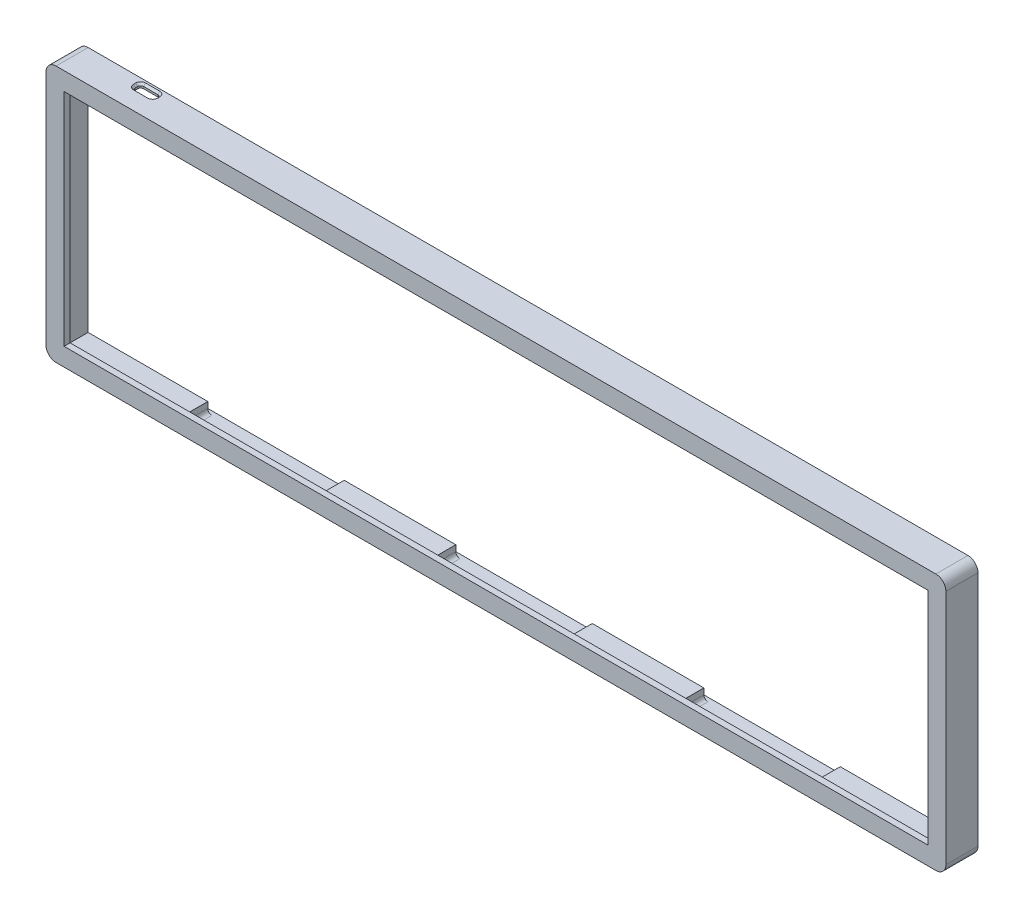
SolidWorks part; units mm, degrees
ref_plane "Front Plane" through (0, 0, 0) normal (0, 0, 1) x (1, 0, 0)
ref_plane "Top Plane" through (0, 0, 0) normal (0, 1, 0) x (1, 0, 0)
ref_plane "Right Plane" through (0, 0, 0) normal (1, 0, 0) x (0, 0, -1)
sketch "Sketch1" plane through (0, 0, 0) normal (0, 0, 1) x (1, 0, 0)
  line L0 (306.936, 114) -> (374.936, 114)
  line L1 (0, 0) -> (434.581, 0)
  line L2 (0, 0) -> (0, 114)
  line L3 (0, 114) -> (434.581, 114)
  line L4 (434.581, 0) -> (434.581, 114)
  line L5 (-2, -7) -> (436.581, -7)
  line L6 (-7, -2) -> (-7, 116)
  line L7 (-2, 121) -> (436.581, 121)
  line L8 (441.581, -2) -> (441.581, 116)
  line L9 (374.936, 114) -> (306.936, 114)
  line L10 (374.936, 114) -> (374.936, 117)
  line L11 (372.936, 119) -> (308.936, 119)
  line L12 (306.936, 114) -> (306.936, 117)
  line L13 (183.291, 114) -> (251.291, 114)
  line L14 (251.291, 114) -> (183.291, 114)
  line L15 (251.291, 114) -> (251.291, 117)
  line L16 (249.291, 119) -> (185.291, 119)
  line L17 (183.291, 114) -> (183.291, 117)
  line L18 (59.646, 0) -> (127.646, 0)
  line L19 (59.646, 0) -> (127.646, 0)
  line L20 (59.646, 0) -> (59.646, -3)
  line L21 (61.646, -5) -> (125.646, -5)
  line L22 (127.646, 0) -> (127.646, -3)
  line L23 (59.646, 114) -> (127.646, 114)
  line L24 (127.646, 114) -> (59.646, 114)
  line L25 (127.646, 114) -> (127.646, 117)
  line L26 (125.646, 119) -> (61.646, 119)
  line L27 (59.646, 114) -> (59.646, 117)
  line L29 (183.291, 0) -> (251.291, 0)
  line L30 (183.291, 0) -> (183.291, -3)
  line L31 (185.291, -5) -> (249.291, -5)
  line L32 (251.291, 0) -> (251.291, -3)
  line L33 (306.936, 0) -> (374.936, 0)
  line L34 (306.936, 0) -> (306.936, -3)
  line L35 (308.936, -5) -> (372.936, -5)
  line L36 (374.936, 0) -> (374.936, -3)
  arc A0 (372.936, 119) -> (374.936, 117) centre (372.936, 117) cw
  arc A1 (308.936, 119) -> (306.936, 117) centre (308.936, 117) ccw
  arc A2 (249.291, 119) -> (251.291, 117) centre (249.291, 117) cw
  arc A3 (185.291, 119) -> (183.291, 117) centre (185.291, 117) ccw
  arc A4 (125.646, -5) -> (127.646, -3) centre (125.646, -3) ccw
  arc A5 (61.646, -5) -> (59.646, -3) centre (61.646, -3) cw
  arc A6 (125.646, 119) -> (127.646, 117) centre (125.646, 117) cw
  arc A7 (61.646, 119) -> (59.646, 117) centre (61.646, 117) ccw
  arc A8 (249.291, -5) -> (251.291, -3) centre (249.291, -3) ccw
  arc A9 (183.291, -3) -> (185.291, -5) centre (185.291, -3) ccw
  arc A10 (372.936, -5) -> (374.936, -3) centre (372.936, -3) ccw
  arc A11 (306.936, -3) -> (308.936, -5) centre (308.936, -3) ccw
  arc A12 (-2, -7) -> (-7, -2) centre (-2, -2) cw
  arc A13 (436.581, -7) -> (441.581, -2) centre (436.581, -2) ccw
  arc A14 (436.581, 121) -> (441.581, 116) centre (436.581, 116) cw
  arc A15 (-7, 116) -> (-2, 121) centre (-2, 116) cw
  point P15 (374.936, 119)
  point P18 (306.936, 119)
  point P33 (127.646, -5)
  point P44 (59.646, -5)
  dimension "D10" = 2
  dimension "D19" = 2
  dimension "D20" = 2
  dimension "D21" = 2
  dimension "D22" = 5
  dimension "D1" = 434.581
  dimension "D2" = 114
  dimension "D3" = 7
  dimension "D4" = 7
  dimension "D5" = 7
  dimension "D6" = 7
  dimension "D7" = 68
  dimension "D8" = 59.645
  dimension "D9" = 5
  dimension "D11" = 0
  dimension "D12" = 55.645
  dimension "D13" = 55.645
  dimension "D14" = 0
  dimension "D15" = 5
  dimension "D16" = 5
  dimension "D17" = 68
  dimension "D18" = 5
extrude "Boss-Extrude1" add sketch "Sketch1" along normal blind 16 contours A15 L6 A12 L5 A13 L8 A14 L7 A11 L34 L1 L32 A8 L31 A9 L30 L22 A4 L21 A5 L20 L2 L3 L27 A7 L26 A6 L25 L17 A3 L16 A2 L15 L12 A1 L11 A0 L10 L4 L36 A10 L35
sketch "Sketch2" plane through (0, 0, 16) normal (0, 0, 1) x (1, 0, 0)
  line L1 (-2, 121) -> (436.581, 121)
  line L2 (-2, 121) -> (-2, -7)
  line L3 (-2, -7) -> (436.581, -7)
  line L4 (436.581, 121) -> (436.581, -7)
  line L10 (127.646, 114) -> (183.291, 114) construction
  line L11 (2, 112) -> (432.581, 112)
  line L12 (2, 112) -> (2, 2)
  line L13 (2, 2) -> (432.581, 2)
  line L14 (432.581, 112) -> (432.581, 2)
  line L15 (0, 0) -> (0, 114) construction
  line L16 (434.581, 0) -> (434.581, 114) construction
  line L17 (374.936, 0) -> (434.581, 0) construction
  dimension "D1" = 2
  dimension "D2" = 2
  dimension "D3" = 2
  dimension "D4" = 2
extrude "Boss-Extrude2" add sketch "Sketch2" against normal blind 3
sketch "Sketch3" plane through (0, 0, 0) normal (0, 0, -1) x (-1, 0, 0)
  line L0 (-372.936, 119) -> (-308.936, 119) construction
  line L1 (-437.581, 119) -> (3.0013, 119)
  line L2 (-437.581, 119) -> (-437.581, -5)
  line L3 (-437.581, -5) -> (3.0013, -5)
  line L4 (3.0013, 119) -> (3.0013, -5)
  line L5 (-434.581, 0) -> (-434.581, 114) construction
  line L6 (0, 0) -> (0, 114) construction
  line L7 (0, 0) -> (-59.646, 0) construction
  dimension "D1" = 0
  dimension "D2" = 3
  dimension "D3" = 3.0013
  dimension "D4" = 5
extrude "Cut-Extrude1" cut sketch "Sketch3" against normal blind 2
sketch "Sketch4" plane through (0, 0, 2) normal (0, 0, -1) x (-1, 0, 0)
  line L0 (-251.291, 114) -> (-306.936, 114) construction
  line L1 (-279.1135, 114) -> (-279.1135, 119) construction
  line L2 (-249.291, 119) -> (-308.936, 119) construction
  line L3 (-155.4685, 114) -> (-155.4685, 119) construction
  line L4 (-127.646, 114) -> (-183.291, 114) construction
  line L5 (-125.646, 119) -> (-185.291, 119) construction
  line L6 (-279.1135, -5) -> (-279.1135, 0) construction
  line L7 (-308.936, -5) -> (-249.291, -5) construction
  line L8 (-306.936, 0) -> (-251.291, 0) construction
  line L9 (-155.4685, 0) -> (-155.4685, -5) construction
  line L10 (-183.291, 0) -> (-127.646, 0) construction
  line L11 (-185.291, -5) -> (-125.646, -5) construction
  line L12 (-2, 2) -> (-2, 0) construction
  line L13 (-59.646, 0) -> (0, 0) construction
  line L14 (-2, 0) -> (-2, -5) construction
  line L15 (3.0013, -5) -> (-437.581, -5) construction
  line L16 (-2, 112) -> (-2, 114) construction
  line L17 (-59.646, 114) -> (0, 114) construction
  line L18 (-2, 114) -> (-2, 119) construction
  line L19 (-437.581, 119) -> (3.0013, 119) construction
  line L20 (-432.581, 112) -> (-432.581, 114) construction
  line L21 (-374.936, 114) -> (-434.581, 114) construction
  line L22 (-432.581, 114) -> (-432.581, 119) construction
  line L23 (-372.936, 119) -> (-437.581, 119) construction
  line L24 (-432.581, 2) -> (-432.581, 0) construction
  line L25 (-374.936, 0) -> (-434.581, 0) construction
  line L26 (-432.581, 0) -> (-432.581, -5) construction
  line L27 (-437.581, -5) -> (-372.936, -5) construction
  circle A0 centre (-279.1135, 116.5) radius 1.05
  circle A1 centre (-155.4685, 116.5) radius 1.05
  circle A2 centre (-279.1135, -2.5) radius 1.05
  circle A3 centre (-155.4685, -2.5) radius 1.05
  circle A4 centre (-2, -2.5) radius 1.05
  circle A5 centre (-2, 116.5) radius 1.05
  circle A6 centre (-432.581, 116.5) radius 1.05
  circle A7 centre (-432.581, -2.5) radius 1.05
extrude "Cut-Extrude2" cut sketch "Sketch4" against normal blind 2.5
sketch "Sketch5" plane through (0, 0, 2) normal (0, 0, -1) x (-1, 0, 0)
  line L0 (0, 114) -> (-59.646, 114) construction
  line L1 (-17, 114) -> (-47, 114)
  line L2 (-17, 114) -> (-17, 119)
  line L3 (-17, 119) -> (-47, 119)
  line L4 (-47, 114) -> (-47, 119)
  line L5 (0, 0) -> (0, 114) construction
  dimension "D1" = 30
  dimension "D2" = 17
  dimension "D3" = 5
extrude "Cut-Extrude3" cut sketch "Sketch5" against normal blind 6
sketch "Sketch6" plane through (0, 119, 0) normal (0, -1, 0) x (1, 0, 0)
  line L0 (17, 8) -> (47, 8) construction
  line L1 (34.6773, 2) -> (27.6773, 2)
  line L2 (36.1773, 3.5) -> (36.1773, 4.5)
  line L3 (34.6773, 6) -> (27.6773, 6)
  line L4 (26.1773, 3.5) -> (26.1773, 4.5)
  arc A0 (36.1773, 4.5) -> (34.6773, 6) centre (34.6773, 4.5) ccw
  arc A1 (27.6773, 6) -> (26.1773, 4.5) centre (27.6773, 4.5) ccw
  arc A2 (27.6773, 2) -> (26.1773, 3.5) centre (27.6773, 3.5) cw
  arc A3 (34.6773, 2) -> (36.1773, 3.5) centre (34.6773, 3.5) ccw
  point P8 (36.1773, 6)
  point P11 (26.1773, 6)
  point P16 (36.1773, 2)
  dimension "D4" = 1.5
  dimension "D5" = 1.5
  dimension "D1" = 10
  dimension "D2" = 4
  dimension "D3" = 2
extrude "Cut-Extrude4" cut sketch "Sketch6" against normal blind 4
chamfer "Chamfer8" distance 1 angle 45 8 edges at (31.1773, 121, 2) (26.1773, 121, 4) (26.6166, 121, 5.5607) (31.1773, 121, 6) (35.7379, 121, 5.5607) (36.1773, 121, 4) (26.6166, 121, 2.4393) (35.7379, 121, 2.4393)
